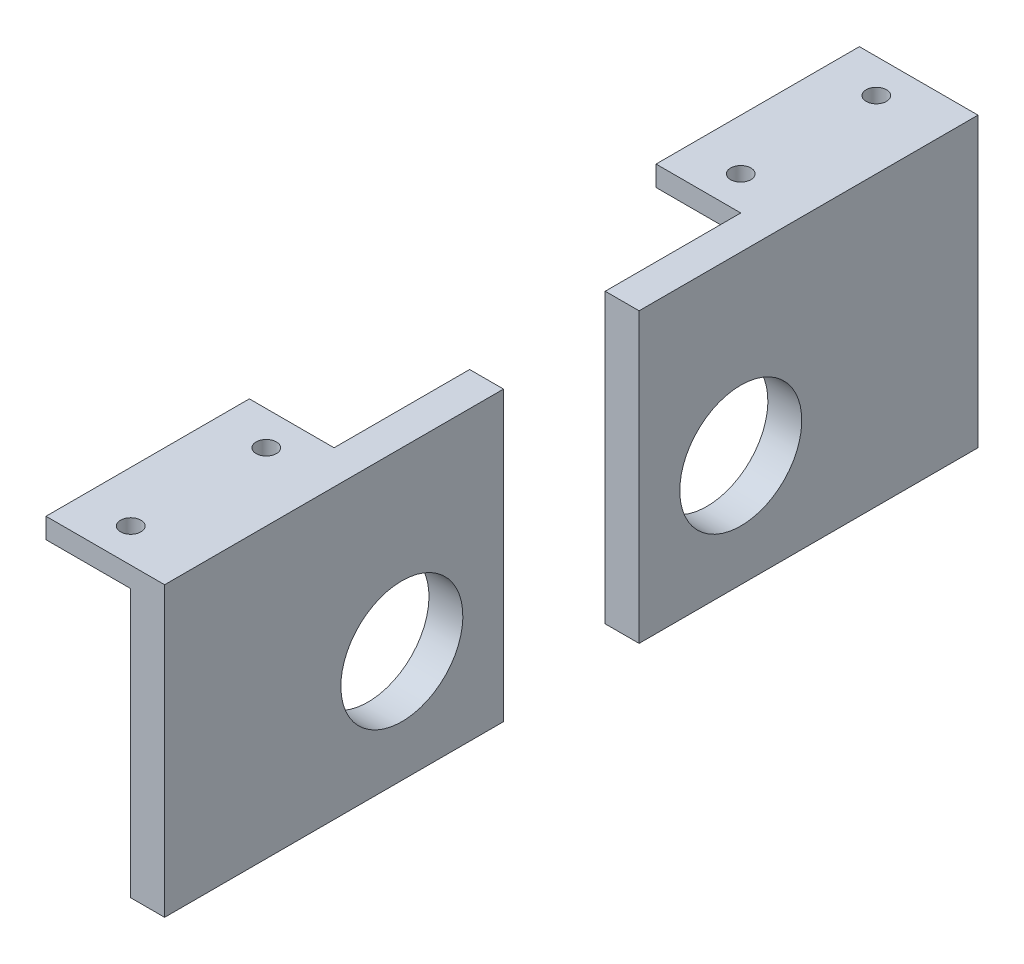
SolidWorks part; units mm, degrees
ref_plane "前视基准面" through (0, 0, 0) normal (0, 0, 1) x (1, 0, 0)
ref_plane "上视基准面" through (0, 0, 0) normal (0, 1, 0) x (1, 0, 0)
ref_plane "右视基准面" through (0, 0, 0) normal (1, 0, 0) x (0, 0, -1)
other "Configuration Table"
sketch "草图1" plane through (0, 0, 0) normal (1, 0, 0) x (0, 0, -1)
  line L0 (-15, -28.5) -> (-15, 11)
  line L2 (-15, 11) -> (15, 11)
  line L4 (-15, -28.5) -> (15, 11) construction
  line L5 (-15, 11) -> (15, -28.5) construction
  line L6 (-15, -28.5) -> (15, -28.5)
  line L7 (15, -28.5) -> (35, -28.5)
  line L8 (15, 11) -> (35, 11)
  line L9 (35, 11) -> (35, -28.5)
  point P0 (0, 0)
  point P2 (0, 0)
extrude "凸台-拉伸1" add sketch "草图1" along normal blind 5 contours L2 L8 L9 L7 L6 L0
sketch3d "3D草图1"
  point P0 (5, -2.7495, 2.7495)
ref_plane "基准面1" through (5, 0, 0) normal (1, 0, 0) x (0, 0, -1)
sketch "草图2" plane through (5, 0, 0) normal (1, 0, 0) x (0, 0, -1)
  circle A0 centre (20, -12) radius 9
extrude "切除-拉伸1" cut sketch "草图2" against normal blind 5
sketch3d "3D草图2"
  point P0 (2.9808, 11, -3.1847)
ref_plane "基准面2" through (0, 11, 0) normal (0, 1, 0) x (1, 0, 0)
sketch "草图3" plane through (0, 11, 0) normal (0, 1, 0) x (1, 0, 0)
  line L0 (5, 15) -> (5, 35)
  line L1 (5, -15) -> (-12.5, -15)
  line L3 (-12.5, 15) -> (-12.5, -15)
  line L4 (5, 15) -> (5, -15)
  line L5 (5, 35) -> (0, 35)
  line L6 (0, 35) -> (0, 15)
  line L7 (0, -15) -> (0, 35) construction
  line L8 (0, 15) -> (-12.5, 15)
extrude "凸台-拉伸2" add sketch "草图3" along normal blind 3
sketch3d "3D草图3"
  point P0 (-6.2094, 14, 4.3134)
ref_plane "基准面4" through (0, 14, 0) normal (0, 1, 0) x (1, 0, 0)
sketch "草图6" plane through (0, 14, 0) normal (0, 1, 0) x (1, 0, 0)
  circle A0 centre (-5, 10) radius 1.5
  circle A1 centre (-5, -10) radius 1.5
extrude "切除-拉伸2" cut sketch "草图6" against normal blind 3
ref_plane "基准面5" through (0, 0, -45) normal (0, 0, -1) x (-1, 0, 0)
mirror "镜向4" about plane through (0, 0, -45) normal (0, 0, -1) of bodies 109
